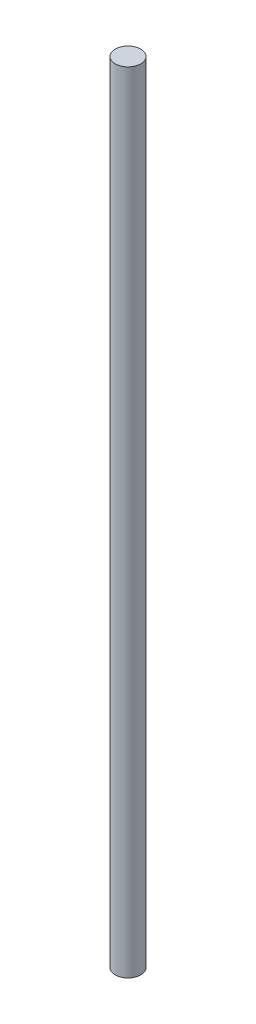
SolidWorks part; units mm, degrees
ref_plane "Front Plane" through (0, 0, 0) normal (0, 0, 1) x (1, 0, 0)
ref_plane "Top Plane" through (0, 0, 0) normal (0, 1, 0) x (1, 0, 0)
ref_plane "Right Plane" through (0, 0, 0) normal (1, 0, 0) x (0, 0, -1)
sketch "Sketch1" plane through (0, 0, 0) normal (0, 1, 0) x (1, 0, 0)
  circle A0 centre (0, 0) radius 4.953
  dimension "D1" = 9.906
extrude "Boss-Extrude1" add sketch "Sketch1" along normal blind 305.562
